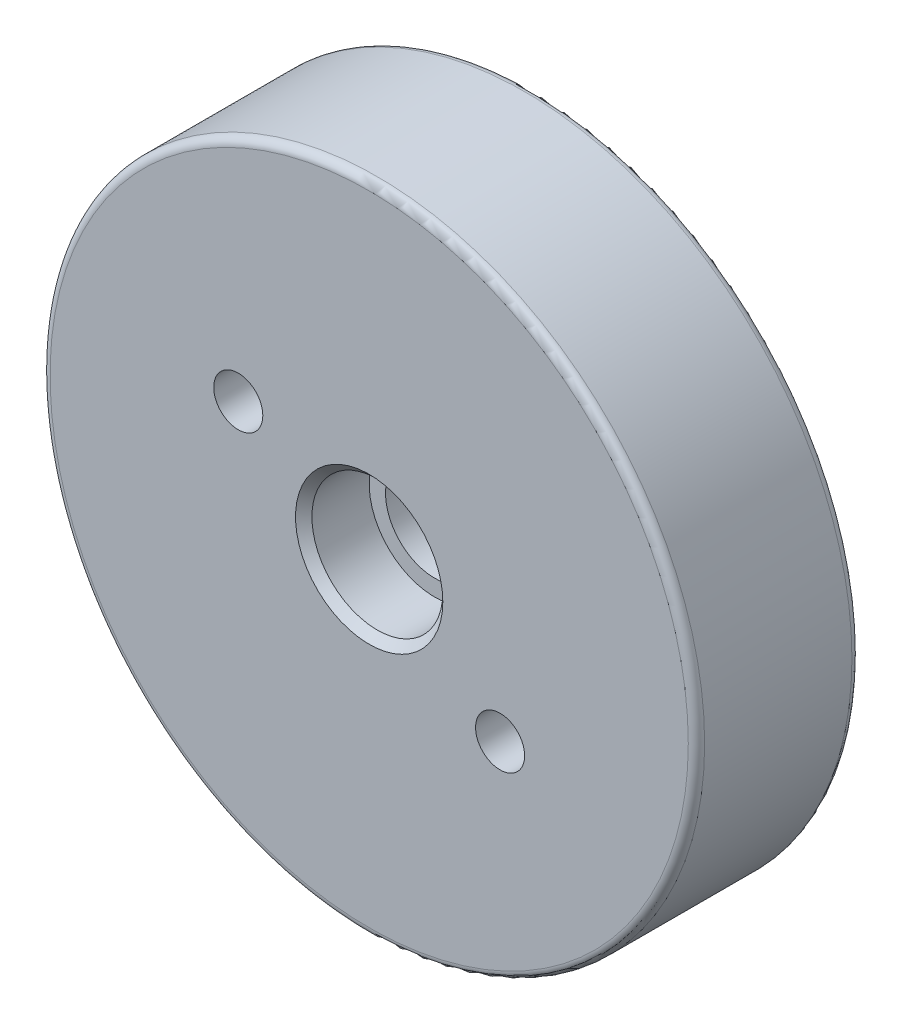
SolidWorks part; units mm, degrees
ref_plane "前视基准面" through (0, 0, 0) normal (0, 0, 1) x (1, 0, 0)
ref_plane "上视基准面" through (0, 0, 0) normal (0, 1, 0) x (1, 0, 0)
ref_plane "右视基准面" through (0, 0, 0) normal (1, 0, 0) x (0, 0, -1)
sketch "草图1" plane through (0, 0, 0) normal (0, 0, 1) x (1, 0, 0)
  circle A0 centre (0, 0) radius 20
  dimension "D1" = 40
extrude "凸台-拉伸1" add sketch "草图1" along normal blind 10
sketch "草图2" plane through (0, 0, 10) normal (0, 0, 1) x (1, 0, 0)
  circle A0 centre (0, 0) radius 3
  dimension "D1" = 6
extrude "切除-拉伸1" cut sketch "草图2" against normal blind 10
sketch "草图3" plane through (0, 0, 10) normal (0, 0, 1) x (1, 0, 0)
  circle A0 centre (0, 0) radius 4
  dimension "D1" = 8
extrude "切除-拉伸2" cut sketch "草图3" against normal blind 4
fillet "圆角1" radius 0.5 2 edges at (20, 0, 0) (20, 0, 10)
chamfer "倒角1" distance 0.5 angle 45 1 edges at (3, 0, 0)
chamfer "倒角2" distance 0.5 angle 45 1 edges at (4, 0, 10)
sketch "草图6" plane through (0, 0, 10) normal (0, 0, 1) x (1, 0, 0)
  circle A0 centre (-8, 4.3538) radius 1.5
  circle A1 centre (8, -5.6462) radius 1.5
  dimension "D4" = 3
  dimension "D5" = 3
extrude "切除-拉伸7" cut sketch "草图6" against normal blind 6
